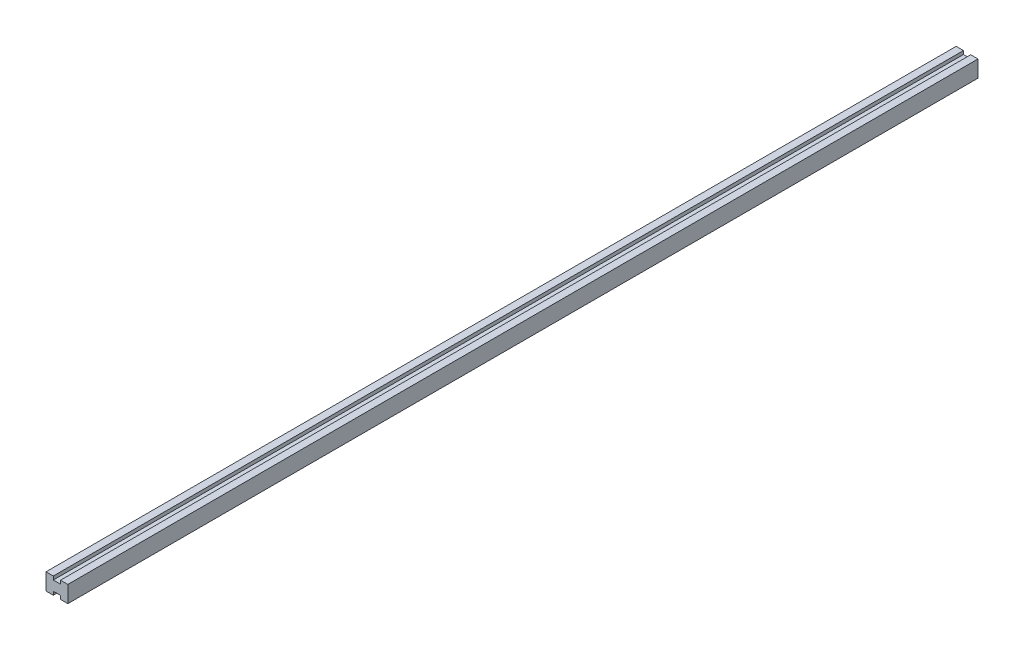
SolidWorks part; units mm, degrees
ref_plane "Front Plane" through (0, 0, 0) normal (0, 0, 1) x (1, 0, 0)
ref_plane "Top Plane" through (0, 0, 0) normal (0, 1, 0) x (1, 0, 0)
ref_plane "Right Plane" through (0, 0, 0) normal (1, 0, 0) x (0, 0, -1)
sketch "Sketch1" plane through (0, 0, 0) normal (0, 0, 1) x (1, 0, 0)
  line L0 (-2.4, 0) -> (0, 0) construction
  line L2 (3.6, -1.6) -> (3.6, 1.6)
  line L4 (-3.6, -1.6) -> (-3.6, 1.6)
  line L5 (3.6, -1.6) -> (-3.6, 1.6) construction
  line L6 (3.6, 1.6) -> (-3.6, -1.6) construction
  line L7 (0, 0) -> (2.4, 0) construction
  line L8 (-1.2, 2.75) -> (-3.6, 2.75)
  line L9 (-1.2, 2.75) -> (-1.2, 1.6)
  line L10 (-1.2, -2.75) -> (-3.6, -2.75)
  line L11 (-3.6, 2.75) -> (-3.6, -2.75)
  line L12 (-1.2, 2.75) -> (-3.6, -2.75) construction
  line L13 (-1.2, -2.75) -> (-3.6, 2.75) construction
  line L14 (-1.2, -1.6) -> (-1.2, -2.75)
  line L15 (1.2, 2.75) -> (3.6, 2.75)
  line L16 (1.2, 2.75) -> (1.2, 1.6)
  line L17 (1.2, -2.75) -> (3.6, -2.75)
  line L18 (3.6, 2.75) -> (3.6, -2.75)
  line L19 (1.2, 2.75) -> (3.6, -2.75) construction
  line L20 (1.2, -2.75) -> (3.6, 2.75) construction
  line L21 (1.2, -1.6) -> (1.2, -2.75)
  line L22 (1.2, -1.6) -> (-1.2, -1.6)
  line L23 (1.2, 1.6) -> (-1.2, 1.6)
  point P0 (0, 0)
  dimension "D1" = 7.2
  dimension "D2" = 3.2
  dimension "D3" = 2.4
  dimension "D4" = 5.5
  dimension "D5" = 2.4
  dimension "D6" = 2.4
  dimension "D7" = 5.5
  dimension "D8" = 2.4
extrude "Boss-Extrude1" add sketch "Sketch1" along normal blind 300 contours L8 L11 L10 L14 L22 L21 L17 L18 L15 L16 L23 L9
